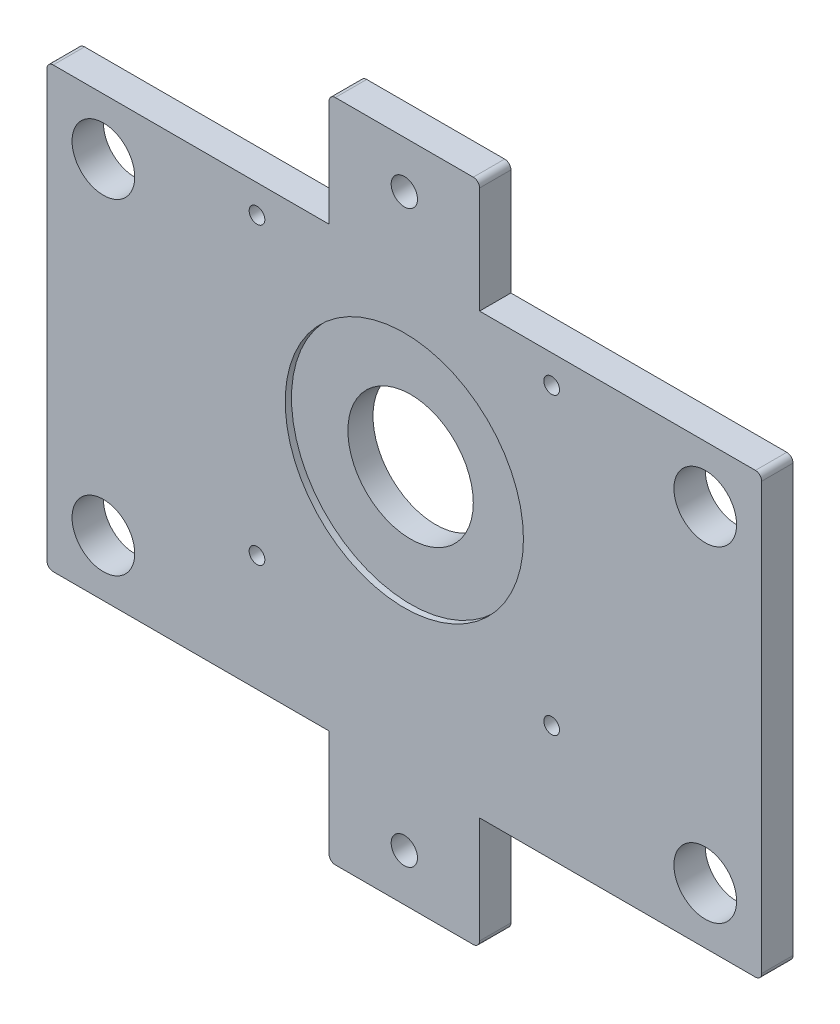
SolidWorks part; units mm, degrees
ref_plane "前视基准面" through (0, 0, 0) normal (0, 0, 1) x (1, 0, 0)
ref_plane "上视基准面" through (0, 0, 0) normal (0, 1, 0) x (1, 0, 0)
ref_plane "右视基准面" through (0, 0, 0) normal (1, 0, 0) x (0, 0, -1)
sketch "草图1" plane through (0, 0, 0) normal (0, 0, 1) x (1, 0, 0)
  line L0 (-57, 35) -> (-57, -35)
  line L1 (-57, -35) -> (-12, -35)
  line L2 (-12, -35) -> (-12, -53)
  line L3 (-12, -53) -> (12, -53)
  line L4 (12, -53) -> (12, -35)
  line L5 (12, -35) -> (57, -35)
  line L6 (57, -35) -> (57, 35)
  line L7 (57, 35) -> (12, 35)
  line L8 (12, 35) -> (12, 53)
  line L9 (12, 53) -> (-12, 53)
  line L10 (-12, 53) -> (-12, 35)
  line L11 (-12, 35) -> (-57, 35)
  line L12 (0, -1000) -> (0, 49000) construction
  line L13 (-1000, 0) -> (49000, 0) construction
  dimension "D1" = 24
  dimension "D2" = 18
  dimension "D3" = 45
  dimension "D4" = 45
  dimension "D5" = 70
  dimension "D6" = 70
  dimension "D7" = 18
  dimension "D8" = 18
  dimension "D9" = 45
  dimension "D10" = 12
  dimension "D11" = 24
  dimension "D12" = 35
extrude "凸台-拉伸1" add sketch "草图1" along normal blind 5
fillet "圆角2" radius 1 8 edges at (12, 53, 2.5) (-12, 53, 2.5) (12, -53, 2.5) (-12, -53, 2.5) (-57, 35, 2.5) (-57, -35, 2.5) (57, -35, 2.5) (57, 35, 2.5)
sketch "草图3" plane through (0, 0, 5) normal (0, 0, 1) x (1, 0, 0)
  line L0 (0, -1000) -> (0, 49000) construction
  line L2 (11, 53) -> (-11, 53) construction
  circle A0 centre (-23.5, 30.5) radius 2 construction
  circle A1 centre (-23.5, -16.5) radius 2 construction
  circle A2 centre (0, 45.5) radius 2 construction
  dimension "D1" = 23.5
  dimension "D2" = 47
  dimension "D4" = 7.5
  dimension "D3" = 22.5
hole_wizard "M3 螺纹孔的螺纹孔钻头1" positions "3D草图1" profile "草图4" hole size "M3" standard "GB" end condition through all
sketch3d "3D草图1"
  point P0 (-23.5, 30.5, 5)
  point P3 (-23.5, -16.5, 5)
sketch "草图4" plane through (-23.5, 30.5, 5) normal (1, 0, 0) x (0, -1, 0)
  line L0 (0, 0) -> (0, 5)
  line L1 (0, 5) -> (1.25, 5)
  line L2 (1.25, 5) -> (1.25, 0)
  line L5 (1.25, 0) -> (0, 0)
  line L11 (0, -6.35) -> (0, 107.95) construction
  dimension "通孔孔直径" = 2.5
  dimension "通孔孔深度" = 5
mirror "镜向1" about plane through (0, 0, 0) normal (1, 0, 0) of "M3 螺纹孔的螺纹孔钻头1"
sketch "草图5" plane through (0, 0, 5) normal (0, 0, 1) x (1, 0, 0)
  line L0 (-57, 34) -> (-57, -34) construction
  line L2 (-12, 35) -> (-56, 35) construction
  circle A0 centre (-48, 26) radius 5
  circle A1 centre (-48, -26) radius 5
  dimension "D1" = 9
  dimension "D3" = 9
  dimension "D2" = 9
  dimension "D4" = 52
extrude "切除-拉伸1" cut sketch "草图5" against normal blind 5
mirror "镜向2" about plane through (0, 0, 0) normal (1, 0, 0) of "切除-拉伸1"
hole_wizard "M5 螺纹孔的螺纹孔钻头1" positions "3D草图3" profile "草图6" hole size "M5" standard "GB" end condition through all
sketch3d "3D草图3"
  point P0 (0, 45.5, 5)
sketch "草图6" plane through (0, 45.5, 5) normal (1, 0, 0) x (0, -1, 0)
  line L0 (0, 0) -> (0, 5)
  line L1 (0, 5) -> (2.1, 5)
  line L2 (2.1, 5) -> (2.1, 0)
  line L5 (2.1, 0) -> (0, 0)
  line L11 (0, -6.35) -> (0, 107.95) construction
  dimension "通孔孔直径" = 4.2
  dimension "通孔孔深度" = 5
mirror "镜向3" about plane through (0, 0, 0) normal (0, 1, 0) of "M5 螺纹孔的螺纹孔钻头1"
sketch "草图7" plane through (0, 0, 5) normal (0, 0, 1) x (1, 0, 0)
  line L1 (0, -201000) -> (0, 249000) construction
  line L2 (11, 53) -> (-11, 53) construction
  circle A0 centre (0, 7) radius 10
  dimension "D1" = 46
extrude "切除-拉伸2" cut sketch "草图7" against normal through all
sketch "草图8" plane through (0, 0, 5) normal (0, 0, 1) x (1, 0, 0)
  circle A0 centre (0, 7) radius 19
extrude "切除-拉伸3" cut sketch "草图8" against normal blind 1
